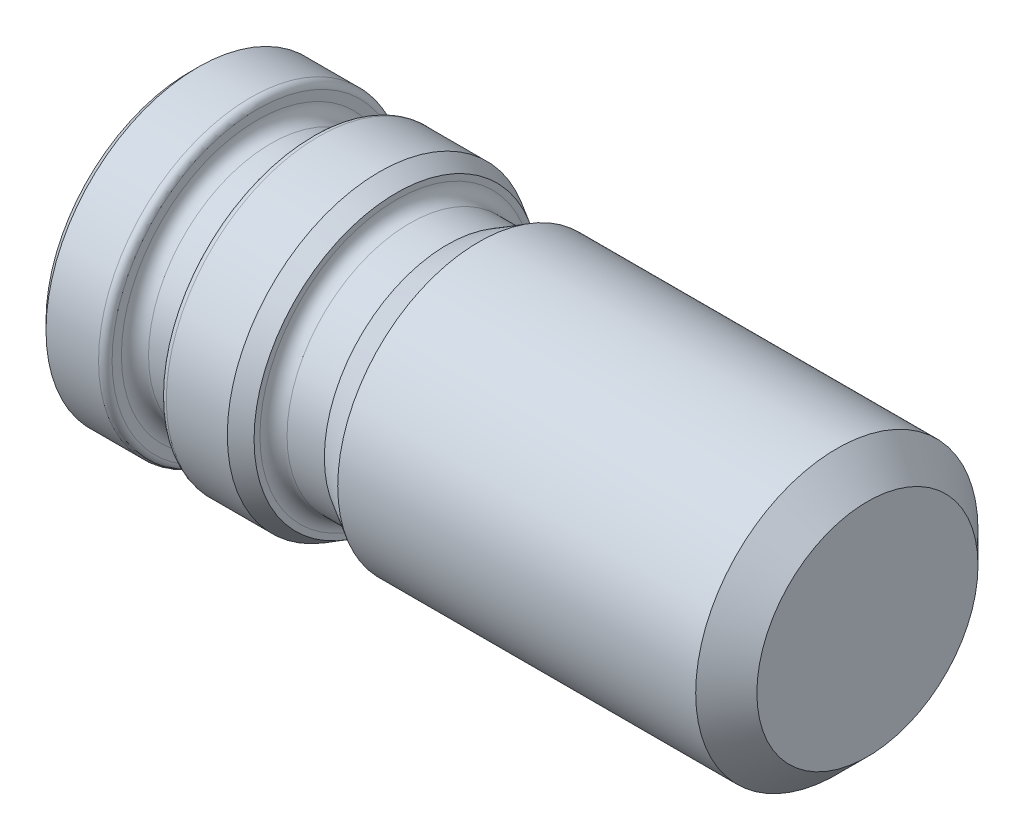
SolidWorks part; units mm, degrees
material "4140 H/T"
ref_plane "Front Plane" through (0, 0, 0) normal (0, 0, 1) x (1, 0, 0)
ref_plane "Top Plane" through (0, 0, 0) normal (0, 1, 0) x (1, 0, 0)
ref_plane "Right Plane" through (0, 0, 0) normal (1, 0, 0) x (0, 0, -1)
sketch "Sketch1" plane through (0, 0, 0) normal (0, 0, 1) x (1, 0, 0)
  line L0 (0, 0) -> (0, 6.525)
  line L1 (0, 6.525) -> (-1.805, 8.33)
  line L2 (-1.805, 8.33) -> (-22.9294, 8.33)
  line L3 (-22.9294, 8.33) -> (-24.8, 7.25)
  line L4 (-24.8, 7.25) -> (-27, 7.25)
  line L5 (-27.8, 8.05) -> (-27.8, 8.975)
  line L6 (-27.8, 8.975) -> (-32.4, 8.975)
  line L7 (-32.8, 8.575) -> (-32.8, 8.025)
  line L8 (-33.6, 7.225) -> (-35.2, 7.225)
  line L9 (-36, 8.025) -> (-36, 8.575)
  line L10 (-36.4, 8.975) -> (-40, 8.975)
  line L11 (-40, 8.975) -> (-40, 0)
  line L12 (-40, 0) -> (0, 0)
  line L13 (0, 0) -> (15.3627, 0) construction
  arc A0 (-32.8, 8.025) -> (-33.6, 7.225) centre (-33.6, 8.025) cw
  arc A1 (-35.2, 7.225) -> (-36, 8.025) centre (-35.2, 8.025) cw
  arc A2 (-32.4, 8.975) -> (-32.8, 8.575) centre (-32.4, 8.575) ccw
  arc A3 (-36, 8.575) -> (-36.4, 8.975) centre (-36.4, 8.575) ccw
  arc A4 (-27, 7.25) -> (-27.8, 8.05) centre (-27, 8.05) cw
  point P17 (-32.8, 7.225)
  point P20 (-36, 7.225)
  dimension "D13" = 0.8
  dimension "D14" = 0.4
  dimension "D15" = 0.8
  dimension "D1" = 40
  dimension "D2" = 17.95
  dimension "D3" = 14.45
  dimension "D4" = 3.2
  dimension "D5" = 4
  dimension "D6" = 12.2
  dimension "D7" = 16.66
  dimension "D8" = 14.5
  dimension "D9" = 30
  dimension "D10" = 3
  dimension "D11" = 45
  dimension "D12" = 13.05
revolve "Revolve1" add sketch "Sketch1" angle 360 about L13
cosmetic thread "Cosmetic Thread1" parameters "D2"=14.95
sketch "Sketch2" plane through (-40, 0, 0) normal (-1, 0, 0) x (0, 0, 1)
  line L1 (2.3671, 4.1) -> (-2.3671, 4.1)
  line L2 (-2.3671, 4.1) -> (-4.7343, 0)
  line L3 (-4.7343, 0) -> (-2.3671, -4.1)
  line L4 (-2.3671, -4.1) -> (2.3671, -4.1)
  line L5 (2.3671, -4.1) -> (4.7343, 0)
  line L6 (4.7343, 0) -> (2.3671, 4.1)
  circle A0 centre (0, 0) radius 4.1 construction
  dimension "D1" = 8.2
extrude "Cut-Extrude1" cut sketch "Sketch2" against normal blind 8
chamfer "Chamfer1" distance 0.5 angle 45 6 edges at (-40, 2.05, -3.5507) (-40, -2.05, -3.5507) (-40, -4.1, 0) (-40, -2.05, 3.5507) (-40, 2.05, 3.5507) (-40, 4.1, 0)
chamfer "Chamfer2" distance 0.5 angle 45 1 edges at (-40, 0, 8.975)
chamfer "Chamfer3" distance 1 angle 30 1 edges at (-27.8, 0, 8.975)
